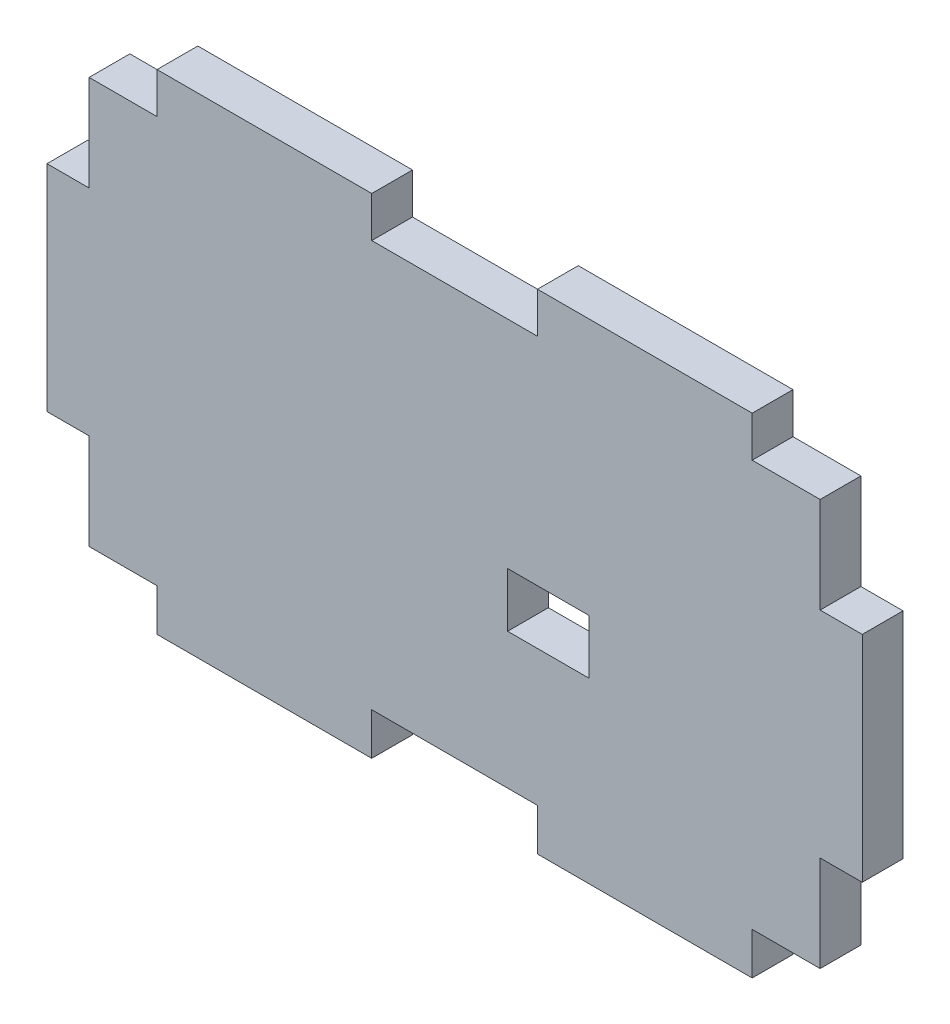
SolidWorks part; units mm, degrees
ref_plane "Front Plane" through (0, 0, 0) normal (0, 0, 1) x (1, 0, 0)
ref_plane "Top Plane" through (0, 0, 0) normal (0, 1, 0) x (1, 0, 0)
ref_plane "Right Plane" through (0, 0, 0) normal (1, 0, 0) x (0, 0, -1)
sketch "Sketch1" plane through (0, 0, 0) normal (0, 0, 1) x (1, 0, 0)
  line L0 (0, 29.9) -> (5, 29.9)
  line L1 (5, -3.1) -> (20.8, -3.1)
  line L2 (-3.1, 7.05) -> (-3.1, 22.85)
  line L3 (5, 32.9) -> (20.8, 32.9)
  line L4 (56.9, 7.05) -> (56.9, 22.85)
  line L5 (5, 29.9) -> (5, 32.9)
  line L6 (5, 32.9) -> (20.8, 32.9)
  line L7 (20.8, 32.9) -> (20.8, 29.9)
  line L8 (20.8, 29.9) -> (33, 29.9)
  line L9 (33, 29.9) -> (33, 32.9)
  line L10 (33, 32.9) -> (48.8, 32.9)
  line L11 (48.8, 32.9) -> (48.8, 29.9)
  line L12 (48.8, 29.9) -> (53.8, 29.9)
  line L13 (53.8, 29.9) -> (53.8, 22.85)
  line L14 (53.8, 22.85) -> (56.9, 22.85)
  line L15 (56.9, 22.85) -> (56.9, 7.05)
  line L16 (56.9, 7.05) -> (53.8, 7.05)
  line L17 (53.8, 7.05) -> (53.8, 0)
  line L18 (53.8, 0) -> (48.8, 0)
  line L19 (48.8, 0) -> (48.8, -3.1)
  line L20 (48.8, -3.1) -> (33, -3.1)
  line L21 (33, -3.1) -> (33, 0)
  line L22 (33, 0) -> (20.8, 0)
  line L23 (20.8, 0) -> (20.8, -3.1)
  line L24 (20.8, -3.1) -> (5, -3.1)
  line L25 (5, -3.1) -> (5, 0)
  line L26 (5, 0) -> (0, 0)
  line L27 (0, 0) -> (0, 7.05)
  line L28 (0, 7.05) -> (-3.1, 7.05)
  line L29 (-3.1, 7.05) -> (-3.1, 22.85)
  line L30 (-3.1, 22.85) -> (0, 22.85)
  line L31 (0, 22.85) -> (0, 29.9)
  line L32 (33, 32.9) -> (48.8, 32.9)
  line L33 (33, -3.1) -> (48.8, -3.1)
  line L35 (30.8, 14) -> (36.8, 14)
  line L36 (30.8, 14) -> (30.8, 10)
  line L37 (30.8, 10) -> (36.8, 10)
  line L38 (36.8, 14) -> (36.8, 10)
  dimension "D1" = 60
  dimension "D2" = 36
  dimension "D3" = 15.8
  dimension "D4" = 12.2
  dimension "D5" = 3
  dimension "D6" = 3.1
  dimension "D7" = 4
  dimension "D8" = 6
  dimension "D9" = 10
  dimension "D10" = 17
extrude "Boss-Extrude1" add sketch "Sketch1" along normal blind 3 contours L31 L30 L2 L28 L27 L26 L25 L1 L23 L22 L21 L20 L19 L18 L17 L16 L4 L14 L13 L12 L11 L10 L9 L8 L7 L3 L5 L0
